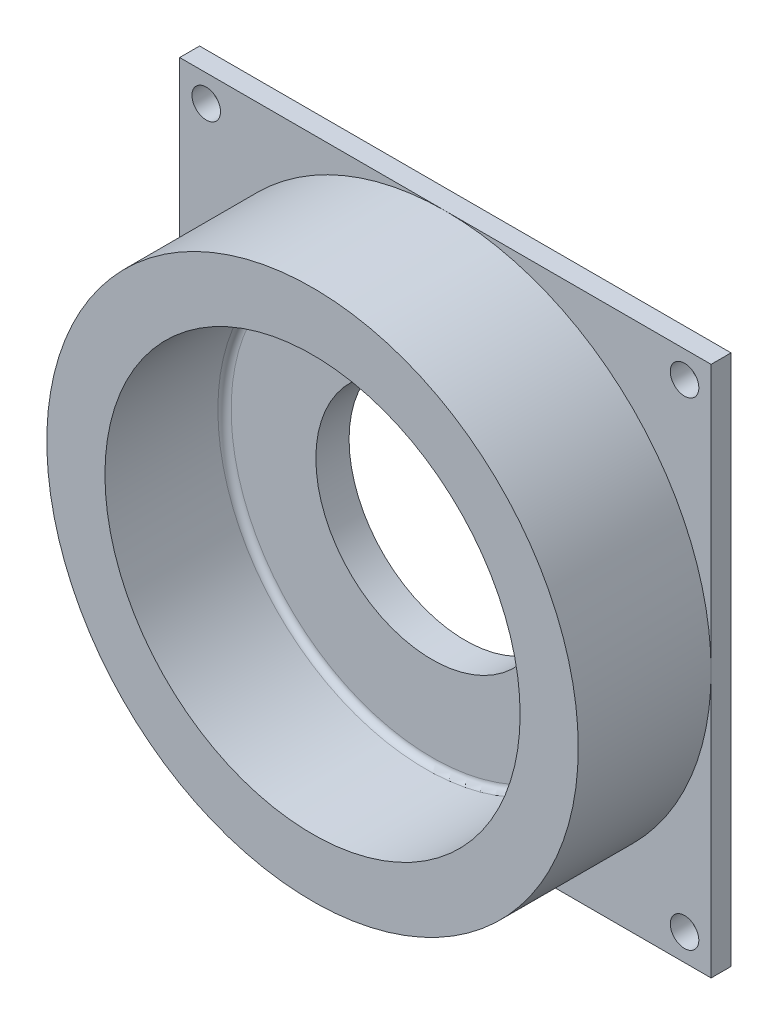
SolidWorks part; units mm, degrees
ref_plane "Plan de face" through (0, 0, 0) normal (0, 0, 1) x (1, 0, 0)
ref_plane "Plan de dessus" through (0, 0, 0) normal (0, 1, 0) x (1, 0, 0)
ref_plane "Plan de droite" through (0, 0, 0) normal (1, 0, 0) x (0, 0, -1)
sketch "Esquisse1" plane through (0, 0, 0) normal (0, 0, 1) x (1, 0, 0)
  circle A0 centre (0, 0) radius 40
  dimension "D1" = 80
extrude "Boss.-Extru.1" add sketch "Esquisse1" along normal blind 20
sketch "Esquisse2" plane through (0, 0, 0) normal (0, 0, 1) x (1, 0, 0)
  circle A0 centre (0, 0) radius 31.25
  dimension "D1" = 62.5
extrude "Enlèv. mat.-Extru.1" cut sketch "Esquisse2" against normal blind 18 from surface at 20 starting at face at (40, 0, 20)
sketch "Esquisse4" plane through (0, 0, 0) normal (0, 0, 1) x (1, 0, 0)
  line L1 (40, -40) -> (-40, -40)
  line L2 (40, -40) -> (40, 40)
  line L3 (40, 40) -> (-40, 40)
  line L4 (-40, -40) -> (-40, 40)
  line L5 (40, -40) -> (-40, 40) construction
  line L6 (40, 40) -> (-40, -40) construction
  point P0 (0, 0)
  dimension "D1" = 80
  dimension "D2" = 80
fillet "Congé3" radius 1 1 edges at (31.25, 0, 2)
extrude "Boss.-Extru.2" add sketch "Esquisse4" against normal blind 3
sketch "Esquisse5" plane through (0, 0, 0) normal (0, 0, 1) x (1, 0, 0)
  circle A0 centre (0, 0) radius 17.5
  dimension "D1" = 35
extrude "Enlèv. mat.-Extru.2" cut sketch "Esquisse5" against normal through all both and the other way through all
hole_wizard "Dégagement M41" positions "Esquisse3D4" profile "Esquisse10" hole size "M4" standard "ISO" end condition through all
sketch3d "Esquisse3D4"
  line L0 (-40, 40, 0) -> (-40, 0, 0) construction
  line L1 (0, 40, 0) -> (-40, 40, 0) construction
  point P0 (-36, 36, 0)
  dimension "D1" = 4
  dimension "D2" = 4
sketch "Esquisse10" plane through (-36, 36, 0) normal (1, 0, 0) x (0, -1, 0)
  line L0 (0, 0) -> (0, 3)
  line L1 (0, 3) -> (2.15, 3)
  line L2 (2.15, 3) -> (2.15, 0)
  line L5 (2.15, 0) -> (0, 0)
  line L11 (0, -6.35) -> (0, 107.95) construction
  dimension "Diamètre du perçage jusqu'au prochain" = 4.3
  dimension "Profondeur du perçage jusqu'au prochain" = 3
mirror "Symétrie1" about plane through (0, 0, 0) normal (1, 0, 0) of "Dégagement M41"
mirror "Symétrie2" about plane through (0, 0, 0) normal (0, 1, 0) of "Symétrie1", "Dégagement M41"
